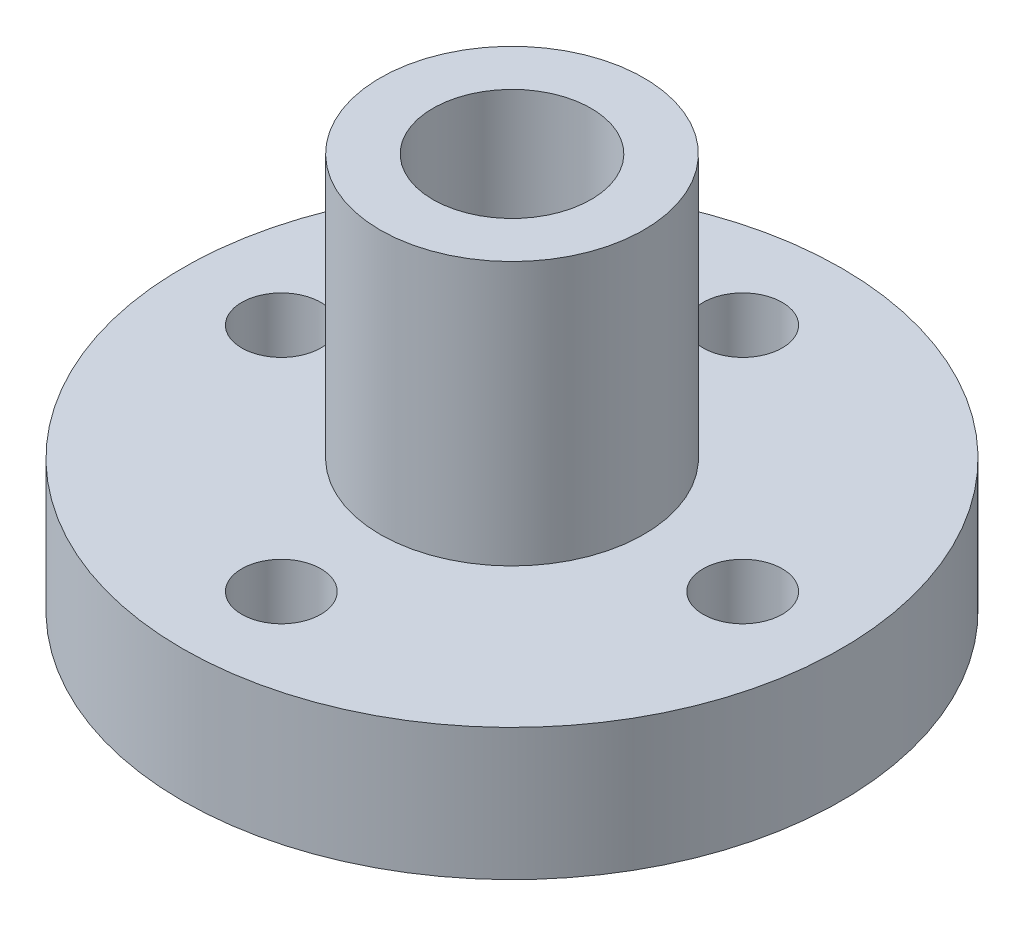
SolidWorks part; units mm, degrees
ref_plane "Front Plane" through (0, 0, 0) normal (0, 0, 1) x (1, 0, 0)
ref_plane "Top Plane" through (0, 0, 0) normal (0, 1, 0) x (1, 0, 0)
ref_plane "Right Plane" through (0, 0, 0) normal (1, 0, 0) x (0, 0, -1)
sketch "Sketch1" plane through (0, 0, 0) normal (0, 1, 0) x (1, 0, 0)
  circle A0 centre (0, 0) radius 5
  circle A1 centre (0, 0) radius 3
  dimension "D1" = 6
  dimension "D2" = 10
extrude "Boss-Extrude1" add sketch "Sketch1" against normal blind 10
sketch "Sketch2" plane through (0, -10, 0) normal (0, -1, 0) x (1, 0, 0)
  circle A0 centre (0, 0) radius 12.5
  dimension "D1" = 25
extrude "Boss-Extrude2" add sketch "Sketch2" along normal blind 5
sketch "Sketch6" plane through (0, -10, 0) normal (0, 1, 0) x (1, 0, 0)
  line L0 (0, 5) -> (0, 12.5) construction
  circle A0 centre (0, 0) radius 5 construction
  circle A1 centre (0, 0) radius 5 construction
  circle A2 centre (0, 0) radius 12.5 construction
  circle A3 centre (0, 8.75) radius 1.5
  circle A4 centre (8.75, 0) radius 1.5
  circle A5 centre (0, -8.75) radius 1.5
  circle A6 centre (-8.75, 0) radius 1.5
  point P20 (0, 0)
  dimension "D1" = 3
  dimension "D2" = 4
extrude "Cut-Extrude1" cut sketch "Sketch6" against normal blind 5
sketch3d "3DSketch1"
  point P0 (-4.9222, -5.749, -0.8787)
ref_plane "Plane3" through (0, 0, -5) normal (0, 0, -1) x (-1, 0, 0)
sketch "Sketch7" plane through (0, 0, -5) normal (0, 0, -1) x (-1, 0, 0)
  line L0 (0, 0) -> (0, -10) construction
  line L1 (12.5, -10) -> (-12.5, -10) construction
  circle A0 centre (0, -5) radius 1.5
  dimension "D1" = 3
extrude "Cut-Extrude2" cut sketch "Sketch7" against normal blind 5
sketch "Sketch8" plane through (0, -10, 0) normal (0, 1, 0) x (1, 0, 0)
  circle A0 centre (0, 0) radius 3
extrude "Cut-Extrude3" cut sketch "Sketch8" against normal blind 5
